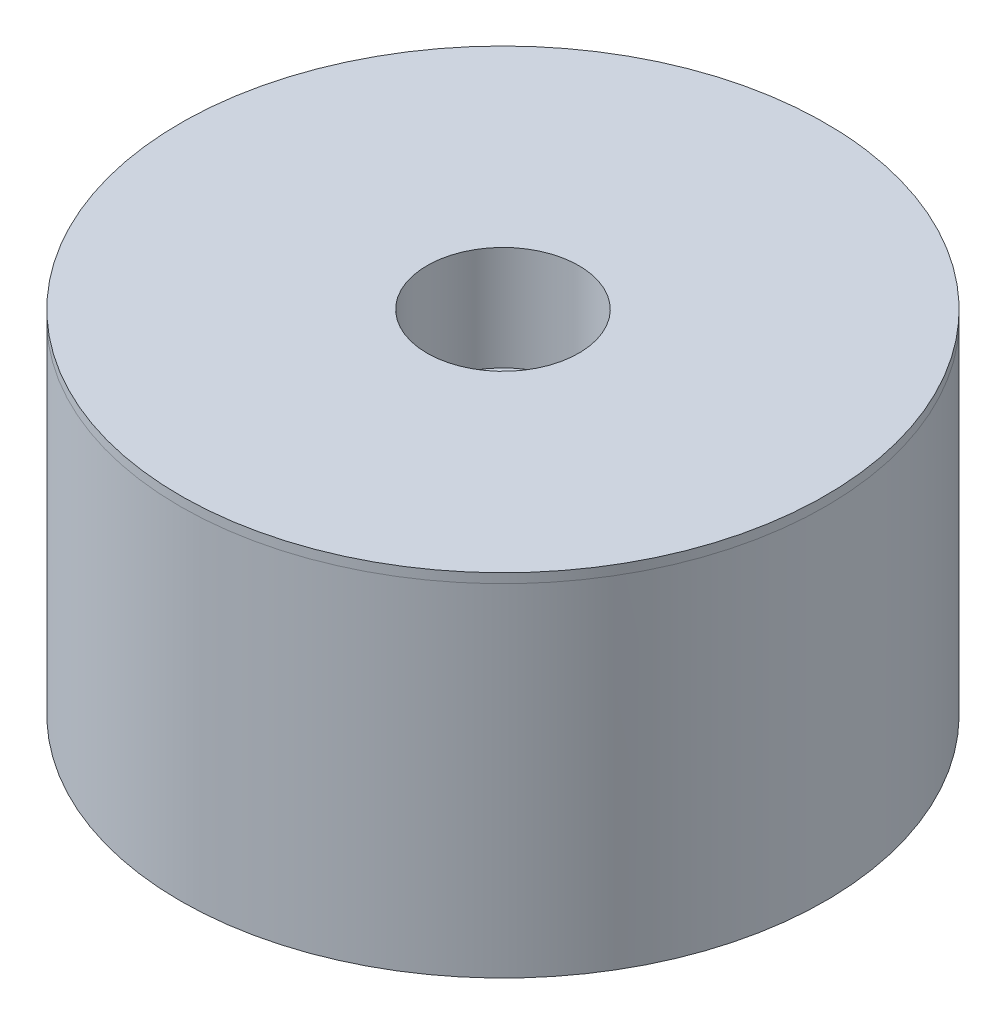
SolidWorks part; units mm, degrees
ref_plane "Front Plane" through (0, 0, 0) normal (0, 0, 1) x (1, 0, 0)
ref_plane "Top Plane" through (0, 0, 0) normal (0, 1, 0) x (1, 0, 0)
ref_plane "Right Plane" through (0, 0, 0) normal (1, 0, 0) x (0, 0, -1)
sketch "Sketch1" plane through (0, 0, 0) normal (0, 1, 0) x (1, 0, 0)
  circle A0 centre (0, 0) radius 17
extrude "Boss-Extrude2" add sketch "Sketch1" along normal blind 18 contours A0
sketch "Sketch3" plane through (0, 18, 0) normal (0, 1, 0) x (1, 0, 0)
  circle A0 centre (0, 0) radius 2.75
extrude "Cut-Extrude2" cut sketch "Sketch3" against normal blind 64 contours A0
sketch "Sketch4" plane through (0, 18, 0) normal (0, 1, 0) x (1, 0, 0)
  circle A0 centre (0, 0) radius 4
extrude "Cut-Extrude3" cut sketch "Sketch4" against normal blind 5 contours A0
sketch "Sketch5" plane through (0, 18, 0) normal (0, 1, 0) x (1, 0, 0)
  circle A0 centre (0, 0) radius 17 construction
  ellipse E0 centre (0, 0) end of major axis (16.9795, -0.8349) minor radius 17
extrude "Boss-Extrude3" add sketch "Sketch5" along normal blind 0.5
sketch "Sketch6" plane through (0, 18.5, 0) normal (0, 1, 0) x (1, 0, 0)
  circle A0 centre (0, 0) radius 4
extrude "Cut-Extrude4" cut sketch "Sketch6" against normal blind 0.5 contours A0
